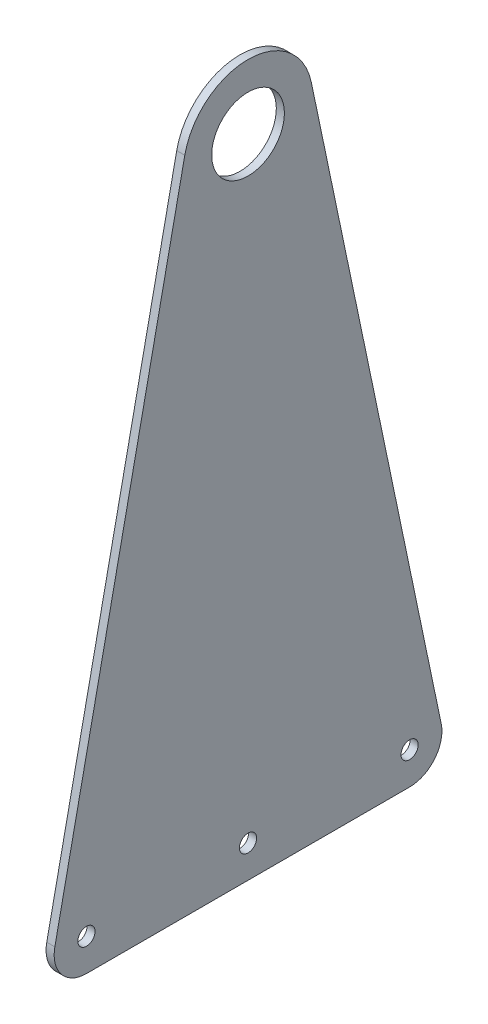
SolidWorks part; units mm, degrees
material "6061 Alloy"
ref_plane "Front" through (0, 0, 0) normal (0, 0, 1) x (1, 0, 0)
ref_plane "Top" through (0, 0, 0) normal (0, 1, 0) x (1, 0, 0)
ref_plane "Right" through (0, 0, 0) normal (1, 0, 0) x (0, 0, -1)
sketch "Sketch1" plane through (0, 0, 0) normal (1, 0, 0) x (0, 0, -1)
  line L0 (-63.5, -241.3) -> (63.5, -241.3) construction
  line L1 (-75.9304, -238.6973) -> (-24.8609, 5.2055)
  line L2 (24.8609, 5.2055) -> (75.9304, -238.6973)
  line L3 (63.5, -254) -> (-63.5, -254)
  circle A0 centre (0, 0) radius 14.2875
  arc A1 (24.8609, 5.2055) -> (-24.8609, 5.2055) centre (0, 0) ccw
  arc A2 (-75.9304, -238.6973) -> (-63.5, -254) centre (-63.5, -241.3) ccw
  arc A3 (63.5, -254) -> (75.9304, -238.6973) centre (63.5, -241.3) ccw
  circle A4 centre (-63.5, -241.3) radius 3.3782
  circle A5 centre (0, -241.3) radius 3.3782
  circle A6 centre (63.5, -241.3) radius 3.3782
  point P12 (0, -241.3)
  dimension "D1" = 28.575
  dimension "D2" = 50.8
  dimension "D3" = 6.7564
  dimension "D6" = 12.7
  dimension "D4" = 254
  dimension "D5" = 127
extrude "Boss-Extrude1" add sketch "Sketch1" along normal blind 3.175
sketch "Sketch2" [suppressed] plane through (3.175, 0, 0) normal (1, 0, 0) x (0, 0, -1)
  line L0 (-17.9605, -94.1605) -> (17.9605, -58.2395) construction
  line L1 (-17.9605, -58.2395) -> (17.9605, -94.1605) construction
  line L2 (-17.9605, -58.2395) -> (-17.9605, -94.1605) construction
  line L3 (-17.9605, -94.1605) -> (17.9605, -94.1605) construction
  circle A0 centre (-17.9605, -58.2395) radius 3.3782
  circle A1 centre (17.9605, -58.2395) radius 2.3812
  circle A2 centre (17.9605, -94.1605) radius 3.3782
  circle A3 centre (-17.9605, -94.1605) radius 2.3812
  circle A4 centre (0, -76.2) radius 19.05
  circle A5 centre (0, 0) radius 14.2875 construction
  point P14 (0, -76.2)
  point P18 (0, -76.2)
  dimension "D2" = 4.7625
  dimension "D3" = 6.7564
  dimension "D4" = 38.1
  dimension "D5" = 76.2
  dimension "D1" = 50.8
extrude "Cut-Extrude1" [suppressed] cut sketch "Sketch2" against normal through all
sketch "Sketch3" [suppressed] plane through (3.175, 0, 0) normal (1, 0, 0) x (0, 0, -1)
  circle A0 centre (0, -76.2) radius 30.1625
  circle A1 centre (0, 0) radius 14.2875 construction
  dimension "D1" = 60.325
  dimension "D2" = 76.2
extrude "Cut-Extrude2" [suppressed] cut sketch "Sketch3" against normal through all
